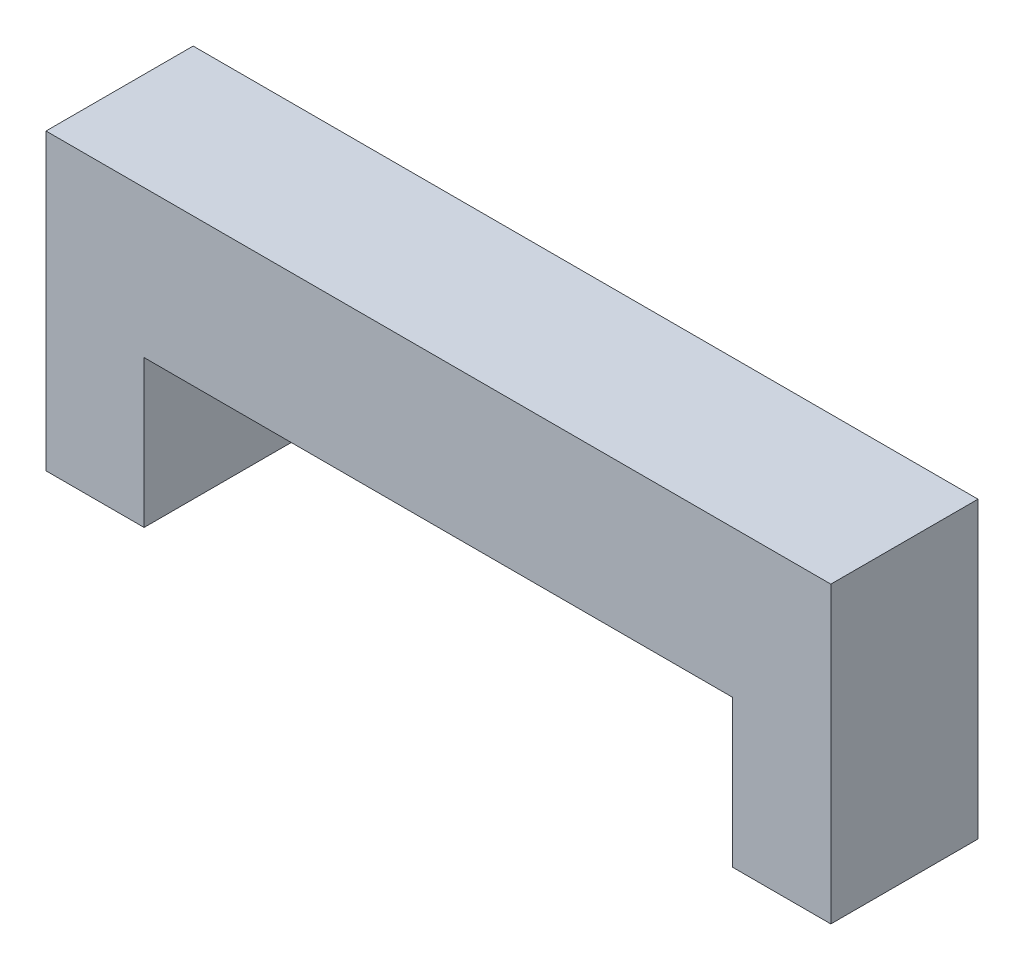
SolidWorks part; units mm, degrees
ref_plane "Front Plane" through (0, 0, 0) normal (0, 0, 1) x (1, 0, 0)
ref_plane "Top Plane" through (0, 0, 0) normal (0, 1, 0) x (1, 0, 0)
ref_plane "Right Plane" through (0, 0, 0) normal (1, 0, 0) x (0, 0, -1)
sketch "Sketch1" plane through (0, 0, 0) normal (0, 0, 1) x (1, 0, 0)
  line L0 (-22.6885, 3.082) -> (-20.6885, 3.082)
  line L1 (-20.6885, 3.082) -> (-20.6885, 6.082)
  line L2 (-20.6885, 6.082) -> (-8.6885, 6.082)
  line L3 (-8.6885, 6.082) -> (-8.6885, 3.082)
  line L4 (-8.6885, 3.082) -> (-6.6885, 3.082)
  line L5 (-6.6885, 3.082) -> (-6.6885, 9.082)
  line L6 (-6.6885, 9.082) -> (-22.6885, 9.082)
  line L7 (-22.6885, 9.082) -> (-22.6885, 3.082)
  point P8 (-7.4426, 6.623)
  dimension "D1" = 2
  dimension "D2" = 16
  dimension "D3" = 6
  dimension "D4" = 3
extrude "Boss-Extrude1" add sketch "Sketch1" along normal blind 3
